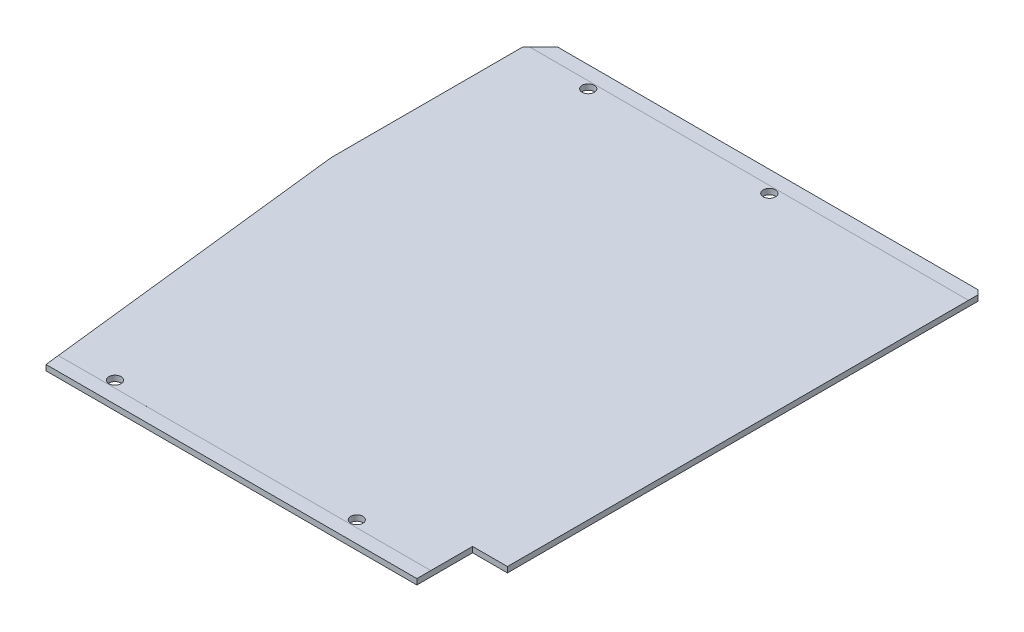
SolidWorks part; units mm, degrees
ref_plane "Front Plane" through (0, 0, 0) normal (0, 0, 1) x (1, 0, 0)
ref_plane "Top Plane" through (0, 0, 0) normal (0, 1, 0) x (1, 0, 0)
ref_plane "Right Plane" through (0, 0, 0) normal (1, 0, 0) x (0, 0, -1)
sketch "Sketch1" plane through (0, 0, 0) normal (0, 1, 0) x (1, 0, 0)
  line L1 (-63.5, 76.2) -> (63.5, 76.2)
  line L2 (-63.5, 76.2) -> (-63.5, -76.2)
  line L3 (-63.5, -76.2) -> (63.5, -76.2)
  line L4 (63.5, 76.2) -> (63.5, -76.2)
  line L5 (-63.5, 76.2) -> (63.5, -76.2) construction
  line L6 (-63.5, -76.2) -> (63.5, 76.2) construction
  point P0 (0, 0)
  dimension "D1" = 127
  dimension "D2" = 152.4
extrude "Boss-Extrude1" add sketch "Sketch1" along normal blind 1.6
chamfer "Chamfer1" distance 5 angle 45 2 edges at (-63.5, 0.8, -76.2) (-63.5, 0.8, 76.2)
chamfer "Chamfer2" distance 1.27 angle 45 2 edges at (63.5, 0.8, 76.2) (63.5, 0.8, -76.2)
sketch "Sketch4" plane through (0, 1.6, 0) normal (0, 1, 0) x (-1, 0, 0)
  line L0 (-72.4805, 72.2) -> (74.1649, 72.2)
  line L3 (58.5, 76.2) -> (-62.23, 76.2) construction
  line L5 (-72.4805, -72.2) -> (74.1649, -72.2)
  line L7 (-62.23, -76.2) -> (58.5, -76.2) construction
  line L9 (-72.4805, 72.2) -> (-72.4805, -72.2)
  line L10 (74.1649, 72.2) -> (74.1649, -72.2)
  dimension "D1" = 4
  dimension "D2" = 4
extrude "Cut-Extrude3" cut sketch "Sketch4" against normal blind 0.0001 flip side to cut
sketch "Sketch5" plane through (0, 1.6, 0) normal (0, 1, 0) x (1, 0, 0)
  line L2 (-53, -76.2) -> (-63.5, 16.2)
  line L3 (-58.5, -76.2) -> (62.23, -76.2) construction
  line L4 (-63.5, 71.2) -> (-63.5, -71.2) construction
  line L5 (62.23, 76.2) -> (-58.5, 76.2) construction
  dimension "D1" = 10.5
  dimension "D2" = 60
extrude "Cut-Extrude4" cut sketch "Sketch5" against normal through all and the other way through all
sketch "Sketch7" plane through (0, 1.6, 0) normal (0, 1, 0) x (1, 0, 0)
  line L0 (-53, -76.2) -> (62.23, -76.2) construction
  line L1 (53.5, -76.2) -> (63.5, -76.2)
  line L2 (53.5, -76.2) -> (53.5, -60.2)
  line L3 (53.5, -60.2) -> (63.5, -60.2)
  line L4 (63.5, -76.2) -> (63.5, -60.2)
  line L5 (63.5, -72.2) -> (63.5, 72.2) construction
  dimension "D1" = 16
  dimension "D2" = 10
extrude "Cut-Extrude7" cut sketch "Sketch7" against normal blind 10
sketch "Sketch9" plane through (0, 1.6, 0) normal (0, 1, 0) x (1, 0, 0)
  line L1 (62.23, 76.2) -> (-58.5, 76.2) construction
  line L2 (63.5, -60.2) -> (63.5, 72.2) construction
  line L3 (-53, -76.2) -> (53.5, -76.2) construction
  line L4 (-63.5, 71.2) -> (-63.5, 16.2) construction
  circle A0 centre (-43.7, 70.2) radius 1.75
  circle A1 centre (8.3, 70.2) radius 1.75
  circle A2 centre (30.252, -70.2) radius 1.75
  circle A3 centre (-39.188, -70.2) radius 1.75
  dimension "D1" = 3.5
  dimension "D2" = 3.5
  dimension "D3" = 3.5
  dimension "D4" = 3.5
  dimension "D6" = 52
  dimension "D5" = 6
  dimension "D7" = 19.8
  dimension "D9" = 6
  dimension "D11" = 33.248
  dimension "D10" = 69.44
  dimension "D8" = 6
extrude "Cut-Extrude8" cut sketch "Sketch9" against normal up to next
